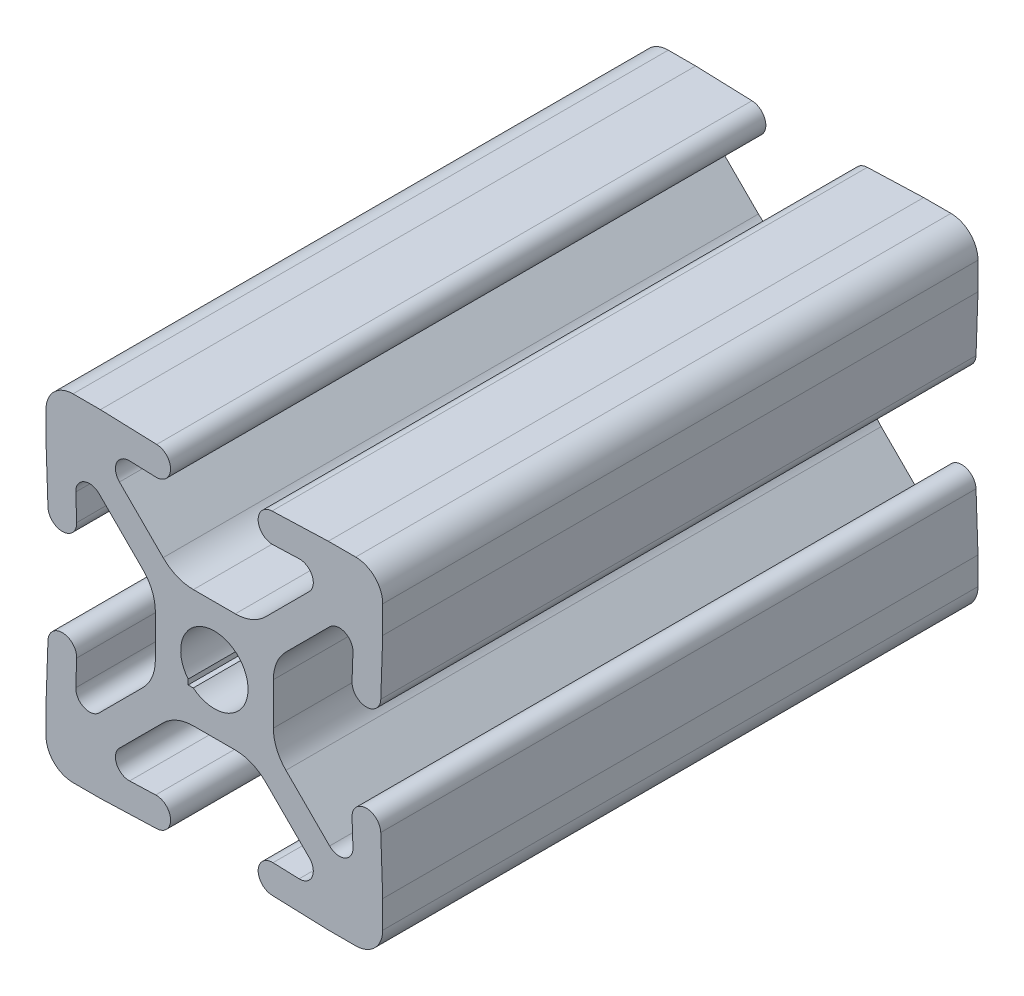
SolidWorks part; units mm, degrees
ref_plane "Front Plane" through (0, 0, 0) normal (0, 0, 1) x (1, 0, 0)
ref_plane "Top Plane" through (0, 0, 0) normal (0, 1, 0) x (1, 0, 0)
ref_plane "Right Plane" through (0, 0, 0) normal (1, 0, 0) x (0, 0, -1)
sketch "Model" plane through (0, 0, 0) normal (0, 0, 1) x (1, 0, 0)
  line L38 (50.6495, 75.4336) -> (50.2699, 75.4336)
  line L39 (50.2699, 75.4336) -> (50.2699, 75.8133)
  line L40 (50.66, 72.9999) -> (53.7746, 72.9999)
  line L41 (56.0196, 72.0699) -> (59.2642, 68.8254)
  line L42 (58.5103, 67.0916) -> (56.5725, 67.1592)
  line L43 (56.498, 65.0269) -> (60.6773, 64.881)
  line L44 (60.6773, 64.881) -> (62.7107, 64.881)
  line L45 (64.7173, 66.8876) -> (64.7173, 68.921)
  line L46 (64.7173, 68.921) -> (64.5713, 73.1002)
  line L47 (62.439, 73.0257) -> (62.5067, 71.0879)
  line L48 (60.7729, 70.334) -> (57.5283, 73.5786)
  line L49 (56.5984, 75.8237) -> (56.5984, 78.9383)
  line L50 (57.5283, 81.1833) -> (60.7729, 84.4279)
  line L51 (62.5067, 83.674) -> (62.439, 81.7362)
  line L52 (64.5713, 81.6617) -> (64.7173, 85.841)
  line L53 (64.7173, 85.841) -> (64.7173, 87.8744)
  line L54 (62.7107, 89.881) -> (60.6773, 89.881)
  line L55 (60.6773, 89.881) -> (56.498, 89.735)
  line L56 (56.5725, 87.6027) -> (58.5103, 87.6704)
  line L57 (59.2642, 85.9366) -> (56.0196, 82.692)
  line L58 (53.7746, 81.7621) -> (50.66, 81.7621)
  line L59 (48.4149, 82.692) -> (45.1703, 85.9366)
  line L60 (45.9242, 87.6704) -> (47.862, 87.6027)
  line L61 (47.9365, 89.735) -> (43.7573, 89.881)
  line L62 (43.7573, 89.881) -> (41.7239, 89.881)
  line L63 (39.7173, 87.8744) -> (39.7173, 85.841)
  line L64 (39.7173, 85.841) -> (39.8632, 81.6617)
  line L65 (41.9955, 81.7362) -> (41.9278, 83.674)
  line L66 (43.6616, 84.4279) -> (46.9062, 81.1833)
  line L67 (47.8361, 78.9383) -> (47.8361, 75.8237)
  line L68 (46.9062, 73.5786) -> (43.6616, 70.334)
  line L69 (41.9278, 71.0879) -> (41.9955, 73.0257)
  line L70 (39.8632, 73.1002) -> (39.7173, 68.921)
  line L71 (39.7173, 68.921) -> (39.7173, 66.8876)
  line L72 (41.7239, 64.881) -> (43.7573, 64.881)
  line L73 (43.7573, 64.881) -> (47.9365, 65.0269)
  line L74 (47.862, 67.1592) -> (45.9242, 67.0916)
  line L75 (45.1703, 68.8254) -> (48.4149, 72.0699)
  arc A29 (50.6495, 75.4336) -> (50.2699, 75.8133) centre (52.2173, 77.381) ccw
  arc A30 (56.0196, 72.0699) -> (53.7746, 72.9999) centre (53.7746, 69.8249) ccw
  arc A31 (58.5103, 67.0916) -> (59.2642, 68.8254) centre (58.5458, 68.1069) ccw
  arc A32 (56.5725, 67.1592) -> (56.498, 65.0269) centre (56.5353, 66.0931) ccw
  arc A33 (62.7107, 64.881) -> (64.7173, 66.8876) centre (62.7107, 66.8876) ccw
  arc A34 (64.5713, 73.1002) -> (62.439, 73.0257) centre (63.5052, 73.063) ccw
  arc A35 (60.7729, 70.334) -> (62.5067, 71.0879) centre (61.4913, 71.0525) ccw
  arc A36 (56.5984, 75.8237) -> (57.5283, 73.5786) centre (59.7734, 75.8237) ccw
  arc A37 (57.5283, 81.1833) -> (56.5984, 78.9383) centre (59.7734, 78.9383) ccw
  arc A38 (62.5067, 83.674) -> (60.7729, 84.4279) centre (61.4913, 83.7095) ccw
  arc A39 (62.439, 81.7362) -> (64.5713, 81.6617) centre (63.5052, 81.699) ccw
  arc A40 (64.7173, 87.8744) -> (62.7107, 89.881) centre (62.7107, 87.8744) ccw
  arc A41 (56.498, 89.735) -> (56.5725, 87.6027) centre (56.5353, 88.6689) ccw
  arc A42 (59.2642, 85.9366) -> (58.5103, 87.6704) centre (58.5458, 86.655) ccw
  arc A43 (53.7746, 81.7621) -> (56.0196, 82.692) centre (53.7746, 84.9371) ccw
  arc A44 (48.4149, 82.692) -> (50.66, 81.7621) centre (50.66, 84.9371) ccw
  arc A45 (45.9242, 87.6704) -> (45.1703, 85.9366) centre (45.8887, 86.655) ccw
  arc A46 (47.862, 87.6027) -> (47.9365, 89.735) centre (47.8993, 88.6689) ccw
  arc A47 (41.7239, 89.881) -> (39.7173, 87.8744) centre (41.7239, 87.8744) ccw
  arc A48 (39.8632, 81.6617) -> (41.9955, 81.7362) centre (40.9293, 81.699) ccw
  arc A49 (43.6616, 84.4279) -> (41.9278, 83.674) centre (42.9432, 83.7095) ccw
  arc A50 (47.8361, 78.9383) -> (46.9062, 81.1833) centre (44.6611, 78.9383) ccw
  arc A51 (46.9062, 73.5786) -> (47.8361, 75.8237) centre (44.6611, 75.8237) ccw
  arc A52 (41.9278, 71.0879) -> (43.6616, 70.334) centre (42.9432, 71.0525) ccw
  arc A53 (41.9955, 73.0257) -> (39.8632, 73.1002) centre (40.9293, 73.063) ccw
  arc A54 (39.7173, 66.8876) -> (41.7239, 64.881) centre (41.7239, 66.8876) ccw
  arc A55 (47.9365, 65.0269) -> (47.862, 67.1592) centre (47.8993, 66.0931) ccw
  arc A56 (45.1703, 68.8254) -> (45.9242, 67.0916) centre (45.8887, 68.1069) ccw
  arc A57 (50.66, 72.9999) -> (48.4149, 72.0699) centre (50.66, 69.8249) ccw
extrude "Boss-Extrude1" add sketch "Model" along normal blind 44.196
